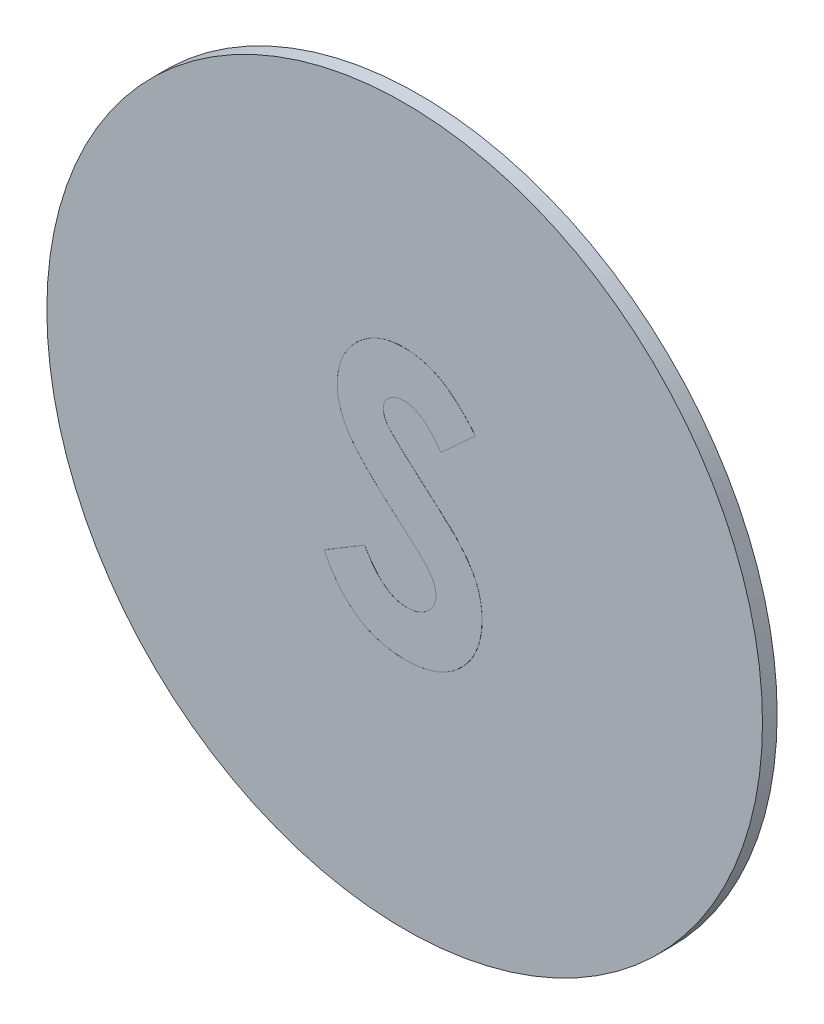
SolidWorks part; units mm, degrees
ref_plane "Front Plane" through (0, 0, 0) normal (0, 0, 1) x (1, 0, 0)
ref_plane "Top Plane" through (0, 0, 0) normal (0, 1, 0) x (1, 0, 0)
ref_plane "Right Plane" through (0, 0, 0) normal (1, 0, 0) x (0, 0, -1)
sketch "Sketch1" plane through (0, 0, 0) normal (0, 0, 1) x (1, 0, 0)
  circle A0 centre (-42.0863, 0) radius 4.88
extrude "Boss-Extrude1" add sketch "Sketch1" along normal blind 0.2
sketch "Sketch2" plane through (0, 0, 0.2) normal (0, 0, 1) x (1, 0, 0)
  text T0 "<b>S</b>"
extrude "Boss-Extrude2" add sketch "Sketch2" along normal blind 0.001
